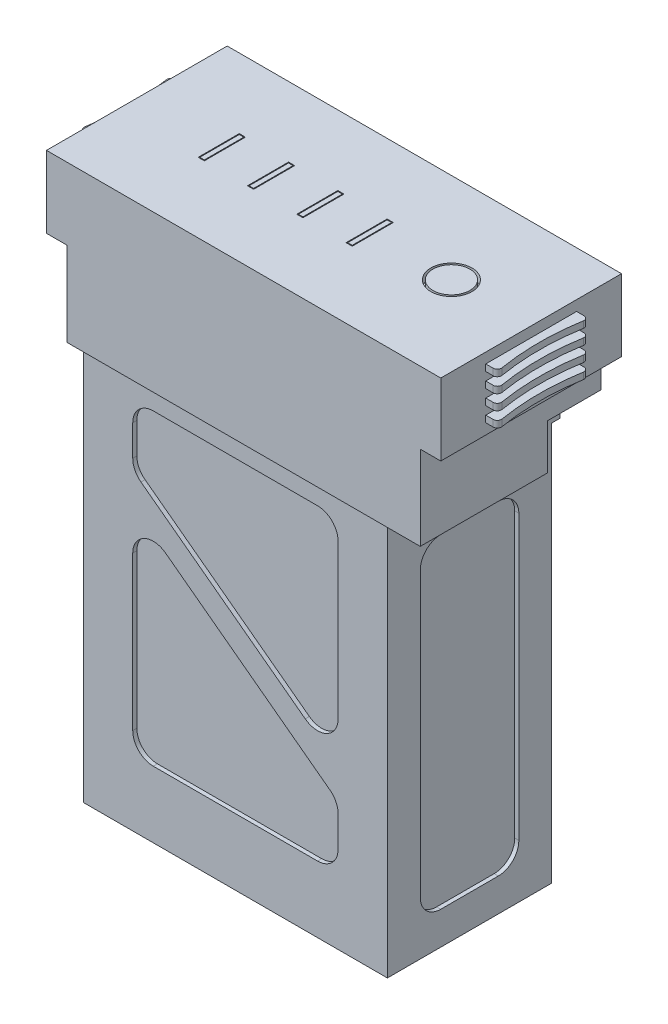
SolidWorks part; units mm, degrees
ref_plane "前视基准面" through (0, 0, 0) normal (0, 0, 1) x (1, 0, 0)
ref_plane "上视基准面" through (0, 0, 0) normal (0, 1, 0) x (1, 0, 0)
ref_plane "右视基准面" through (0, 0, 0) normal (1, 0, 0) x (0, 0, -1)
sketch "草图1" plane through (0, 0, 0) normal (0, 1, 0) x (1, 0, 0)
  line L0 (0, 20) -> (0, -20) construction
  line L1 (-37, 20) -> (37, 20)
  line L2 (-37, 20) -> (-37, -20)
  line L3 (-37, -20) -> (37, -20)
  line L4 (37, 20) -> (37, -20)
  point P6 (0, 0)
  dimension "D1" = 74
  dimension "D2" = 40
extrude "凸台-拉伸1" add sketch "草图1" along normal blind 97
sketch "草图2" plane through (0, 97, 0) normal (0, 1, 0) x (1, 0, 0)
  line L0 (-37, 20) -> (-37, -20) construction
  line L1 (-44, 22) -> (52, 22)
  line L2 (-44, 22) -> (-44, -22)
  line L3 (-44, -22) -> (52, -22)
  line L4 (52, 22) -> (52, -22)
  line L5 (-44, 0) -> (52, 0) construction
  line L6 (-37, 0) -> (37, 0) construction
  line L7 (37, -20) -> (37, 20) construction
  dimension "D1" = 96
  dimension "D2" = 44
  dimension "D3" = 7
extrude "凸台-拉伸2" add sketch "草图2" along normal blind 38
sketch "草图3" plane through (0, 97, 0) normal (0, -1, 0) x (1, 0, 0)
  line L0 (37, -22) -> (37, -9)
  line L1 (52, -22) -> (-44, -22) construction
  line L2 (37, 20) -> (37, -20) construction
  line L3 (37, -9) -> (47, -9)
  line L4 (47, -9) -> (47, -22)
  line L5 (37, -22) -> (47, -22)
extrude "切除-拉伸1" cut sketch "草图3" against normal blind 11
sketch "草图4" plane through (0, 97, 0) normal (0, -1, 0) x (1, 0, 0)
  line L1 (47, -22) -> (52, -22)
  line L2 (47, -22) -> (47, 22)
  line L3 (47, 22) -> (52, 22)
  line L4 (52, -22) -> (52, 22)
extrude "切除-拉伸2" cut sketch "草图4" against normal blind 11
sketch "草图5" plane through (0, 135, 0) normal (0, 1, 0) x (1, 0, 0)
  line L0 (13.4331, 0) -> (11.9331, 0) construction
  line L1 (11.9331, 5) -> (13.4331, 5)
  line L2 (11.9331, 5) -> (11.9331, -5)
  line L3 (11.9331, -5) -> (13.4331, -5)
  line L4 (13.4331, 5) -> (13.4331, -5)
  line L5 (-0.0669, 5) -> (1.4331, 5)
  line L6 (-0.0669, 5) -> (-0.0669, -5)
  line L7 (1.4331, 5) -> (1.4331, -5)
  line L8 (-0.0669, -5) -> (1.4331, -5)
  line L9 (-12.0669, 5) -> (-10.5669, 5)
  line L10 (-12.0669, 5) -> (-12.0669, -5)
  line L11 (-10.5669, 5) -> (-10.5669, -5)
  line L12 (-12.0669, -5) -> (-10.5669, -5)
  line L13 (-24.0669, 5) -> (-22.5669, 5)
  line L14 (-24.0669, 5) -> (-24.0669, -5)
  line L15 (-22.5669, 5) -> (-22.5669, -5)
  line L16 (-24.0669, -5) -> (-22.5669, -5)
  circle A0 centre (32.585, 0) radius 5
  dimension "D1" = 10
  dimension "D2" = 10
  dimension "D3" = 1.5
  dimension "D4" = 4
extrude "切除-拉伸3" cut sketch "草图5" against normal blind 2
sketch "草图6" plane through (0, 133, 0) normal (0, 1, 0) x (1, 0, 0)
  line L8 (-23.8669, 4.8) -> (-23.8669, -4.8)
  line L9 (-23.8669, -4.8) -> (-22.7669, -4.8)
  line L10 (-22.7669, -4.8) -> (-22.7669, 4.8)
  line L11 (-22.7669, 4.8) -> (-23.8669, 4.8)
  line L12 (-23.8669, 4.8) -> (-23.8669, -4.8)
  line L13 (-23.8669, -4.8) -> (-22.7669, -4.8)
  line L14 (-22.7669, -4.8) -> (-22.7669, 4.8)
  line L15 (-22.7669, 4.8) -> (-23.8669, 4.8)
  line L24 (-11.8669, 4.8) -> (-11.8669, -4.8)
  line L25 (-11.8669, -4.8) -> (-10.7669, -4.8)
  line L26 (-10.7669, -4.8) -> (-10.7669, 4.8)
  line L27 (-10.7669, 4.8) -> (-11.8669, 4.8)
  line L28 (-11.8669, 4.8) -> (-11.8669, -4.8)
  line L29 (-11.8669, -4.8) -> (-10.7669, -4.8)
  line L30 (-10.7669, -4.8) -> (-10.7669, 4.8)
  line L31 (-10.7669, 4.8) -> (-11.8669, 4.8)
  line L36 (0.1331, 4.8) -> (0.1331, -4.8)
  line L37 (0.1331, -4.8) -> (1.2331, -4.8)
  line L38 (1.2331, -4.8) -> (1.2331, 4.8)
  line L39 (1.2331, 4.8) -> (0.1331, 4.8)
  line L40 (0.1331, 4.8) -> (0.1331, -4.8)
  line L41 (0.1331, -4.8) -> (1.2331, -4.8)
  line L42 (1.2331, -4.8) -> (1.2331, 4.8)
  line L43 (1.2331, 4.8) -> (0.1331, 4.8)
  line L48 (12.1331, 4.8) -> (12.1331, -4.8)
  line L49 (12.1331, -4.8) -> (13.2331, -4.8)
  line L50 (13.2331, -4.8) -> (13.2331, 4.8)
  line L51 (13.2331, 4.8) -> (12.1331, 4.8)
  line L52 (12.1331, 4.8) -> (12.1331, -4.8)
  line L53 (12.1331, -4.8) -> (13.2331, -4.8)
  line L54 (13.2331, -4.8) -> (13.2331, 4.8)
  line L55 (13.2331, 4.8) -> (12.1331, 4.8)
  circle A0 centre (32.585, 0) radius 4.5
  dimension "D1" = 0.2
  dimension "D2" = 0.2
  dimension "D3" = 0.2
  dimension "D4" = 0.2
extrude "凸台-拉伸3" add sketch "草图6" along normal blind 2
ref_plane "基准面1" through (0, 132.5, 0) normal (0, 1, 0) x (1, 0, 0)
sketch "草图7" plane through (0, 132.5, 0) normal (0, 1, 0) x (1, 0, 0)
  line L0 (-44, -11.0573) -> (-45.8071, -11.0573)
  line L1 (-44, 22) -> (-44, -22) construction
  line L2 (-44, 0) -> (-52.2265, 0) construction
  line L3 (-44, 11.0573) -> (-45.8071, 11.0573)
  line L4 (-44, -11.0573) -> (-44, 11.0573)
  arc A0 (-46.7935, -9.8924) -> (-46.7935, 9.8924) centre (-105.9723, 0) ccw
  arc A1 (-45.8071, 11.0573) -> (-46.7935, 9.8924) centre (-45.8071, 10.0573) ccw
  arc A2 (-45.8071, -11.0573) -> (-46.7935, -9.8924) centre (-45.8071, -10.0573) cw
  point P12 (-47, 11.0573)
  point P15 (-47, -11.0573)
  dimension "D2" = 60
  dimension "D3" = 1
  dimension "D1" = 3
extrude "凸台-拉伸4" add sketch "草图7" against normal blind 1.6
pattern_linear "阵列(线性)1" count 4 spacing 3.6 along (0, -1, 0) of "凸台-拉伸4"
ref_plane "基准面2" through (4, 0, 0) normal (-1, 0, 0) x (0, 0, 1)
mirror "镜向2" about plane through (4, 0, 0) normal (-1, 0, 0) of "阵列(线性)1", "凸台-拉伸4"
sketch "草图8" plane through (-37, 0, 0) normal (-1, 0, 0) x (0, 0, 1)
  line L0 (-20, 97) -> (-20, 0) construction
  line L1 (-7, 87) -> (7, 87)
  line L2 (-12, 82) -> (-12, 13)
  line L3 (-7, 8) -> (7, 8)
  line L4 (12, 82) -> (12, 13)
  line L5 (20, 97) -> (20, 0) construction
  line L6 (-20, 0) -> (20, 0) construction
  line L7 (-20, 97) -> (20, 97) construction
  arc A0 (-12, 13) -> (-7, 8) centre (-7, 13) ccw
  arc A1 (7, 8) -> (12, 13) centre (7, 13) ccw
  arc A2 (12, 82) -> (7, 87) centre (7, 82) ccw
  arc A3 (-12, 82) -> (-7, 87) centre (-7, 82) cw
  dimension "D5" = 5
  dimension "D1" = 8
  dimension "D2" = 8
  dimension "D3" = 8
  dimension "D4" = 10
extrude "切除-拉伸4" cut sketch "草图8" against normal blind 1
ref_plane "基准面3" through (0, 0, 0) normal (1, 0, 0) x (0, 0, -1)
mirror "镜向3" about plane through (0, 0, 0) normal (1, 0, 0) of "切除-拉伸4"
sketch "草图9" plane through (0, 0, -20) normal (0, 0, -1) x (-1, 0, 0)
  line L0 (-20, 91.0672) -> (20, 91.0672)
  line L1 (25, 86.0672) -> (25, 78.5706)
  line L2 (22.9957, 74.5674) -> (-17.0043, 44.6352)
  line L3 (-25, 48.6384) -> (-25, 86.0672)
  line L4 (-22.9957, 32.6579) -> (17.0043, 62.5901)
  line L5 (25, 58.5869) -> (25, 21.1581)
  line L6 (20, 16.1581) -> (-20, 16.1581)
  line L7 (-25, 21.1581) -> (-25, 28.6547)
  line L8 (-37, 97) -> (-37, 0) construction
  arc A0 (-22.9957, 32.6579) -> (-25, 28.6547) centre (-20, 28.6547) ccw
  arc A1 (-25, 48.6384) -> (-17.0043, 44.6352) centre (-20, 48.6384) ccw
  arc A2 (-25, 86.0672) -> (-20, 91.0672) centre (-20, 86.0672) cw
  arc A3 (22.9957, 74.5674) -> (25, 78.5706) centre (20, 78.5706) ccw
  arc A4 (25, 86.0672) -> (20, 91.0672) centre (20, 86.0672) ccw
  arc A5 (-25, 21.1581) -> (-20, 16.1581) centre (-20, 21.1581) ccw
  arc A6 (25, 21.1581) -> (20, 16.1581) centre (20, 21.1581) cw
  arc A7 (25, 58.5869) -> (17.0043, 62.5901) centre (20, 58.5869) ccw
  point P12 (-25, 31.1581)
  point P17 (-25, 91.0672)
  point P20 (25, 76.0672)
  point P23 (25, 91.0672)
  point P26 (-25, 16.1581)
  point P29 (25, 16.1581)
  dimension "D8" = 5
  dimension "D9" = 5
  dimension "D1" = 15
  dimension "D2" = 15
  dimension "D3" = 50
  dimension "D4" = 50
  dimension "D5" = 12
  dimension "D6" = 12
  dimension "D7" = 6
extrude "切除-拉伸5" cut sketch "草图9" against normal blind 1
ref_plane "基准面4" through (0, 0, 0) normal (0, 0, 1) x (1, 0, 0)
mirror "镜向4" about plane through (0, 0, 0) normal (0, 0, 1) of "切除-拉伸5"
sketch "草图10" plane through (0, 0, -22) normal (0, 0, -1) x (-1, 0, 0)
  line L1 (44, 97) -> (39, 97)
  line L2 (44, 97) -> (44, 117.5)
  line L3 (44, 117.5) -> (39, 117.5)
  line L4 (39, 97) -> (39, 117.5)
  line L5 (-52, 108) -> (-47, 108)
  line L6 (-52, 108) -> (-52, 117.5)
  line L7 (-52, 117.5) -> (-47, 117.5)
  line L8 (-47, 108) -> (-47, 117.5)
  dimension "D1" = 20.5
  dimension "D2" = 5
extrude "切除-拉伸6" cut sketch "草图10" against normal through all
